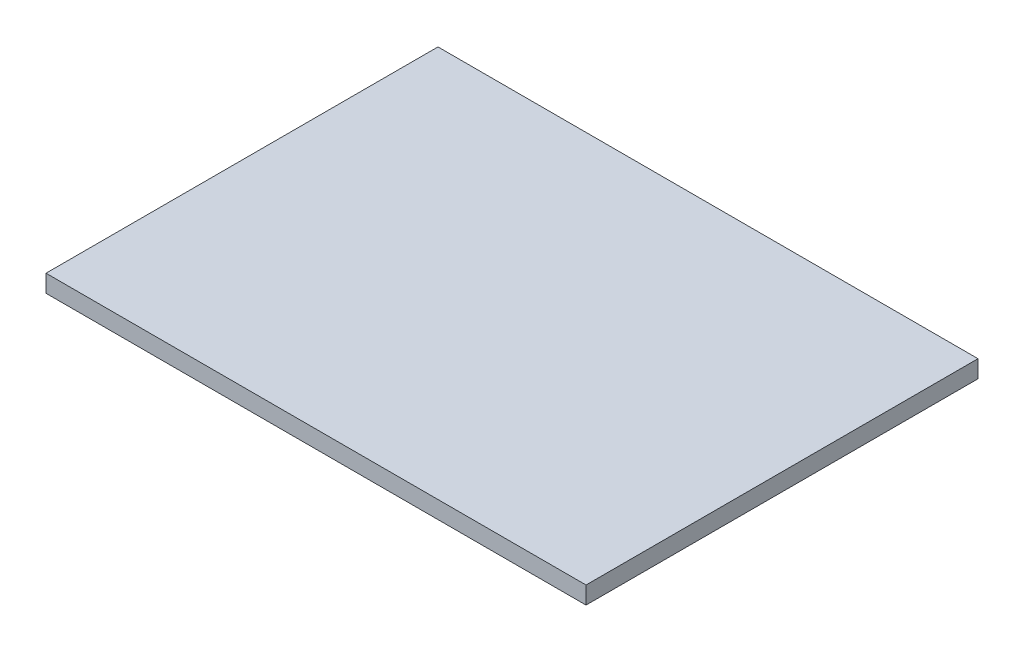
SolidWorks part; units mm, degrees
ref_plane "Front" through (0, 0, 0) normal (0, 0, 1) x (1, 0, 0)
ref_plane "Top" through (0, 0, 0) normal (0, 1, 0) x (1, 0, 0)
ref_plane "Right" through (0, 0, 0) normal (1, 0, 0) x (0, 0, -1)
sketch "Sketch1" plane through (0, 0, 0) normal (0, 1, 0) x (1, 0, 0)
  line L1 (-31, -22.5) -> (31, -22.5)
  line L2 (-31, -22.5) -> (-31, 22.5)
  line L3 (-31, 22.5) -> (31, 22.5)
  line L4 (31, -22.5) -> (31, 22.5)
  line L5 (-31, -22.5) -> (31, 22.5) construction
  line L6 (-31, 22.5) -> (31, -22.5) construction
  point P0 (0, 0)
  dimension "D1" = 62
  dimension "D2" = 45
extrude "Boss-Extrude1" add sketch "Sketch1" along normal blind 2
